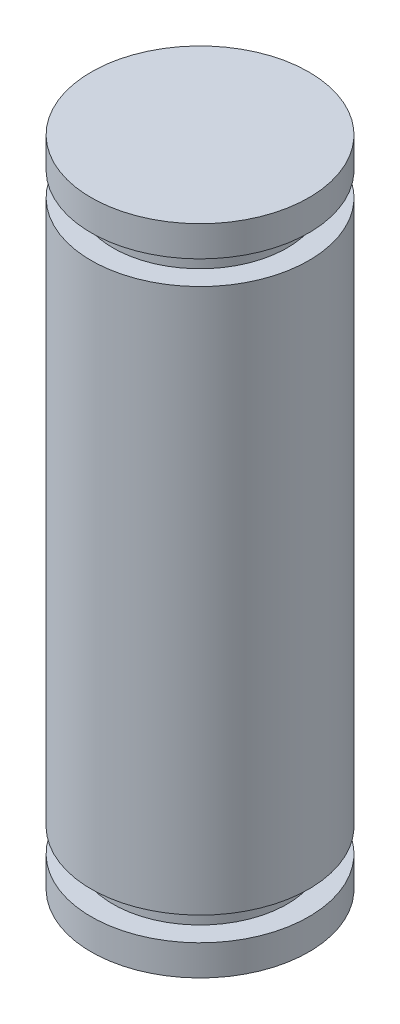
SolidWorks part; units mm, degrees
ref_plane "前视基准面" through (0, 0, 0) normal (0, 0, 1) x (1, 0, 0)
ref_plane "上视基准面" through (0, 0, 0) normal (0, 1, 0) x (1, 0, 0)
ref_plane "右视基准面" through (0, 0, 0) normal (1, 0, 0) x (0, 0, -1)
sketch "草图1" plane through (0, 0, 0) normal (0, 0, 1) x (1, 0, 0)
  line L0 (0, 0) -> (0, 30) construction
  line L1 (0, 0) -> (-5, 0)
  line L2 (-5, 0) -> (-5, 1.4)
  line L3 (-5, 1.4) -> (-4, 1.4)
  line L4 (-4, 1.4) -> (-4, 2.5)
  line L5 (-4, 2.5) -> (-5, 2.5)
  line L6 (-5, 2.5) -> (-5, 27.5)
  line L7 (-5, 27.5) -> (-4, 27.5)
  line L8 (-4, 27.5) -> (-4, 28.6)
  line L9 (-4, 28.6) -> (-5, 28.6)
  line L10 (-5, 28.6) -> (-5, 30)
  line L11 (-5, 30) -> (0, 30)
  line L12 (0, 0) -> (0, 30)
  dimension "D1" = 25
  dimension "D2" = 30
  dimension "D3" = 1.1
  dimension "D4" = 1.1
  dimension "D5" = 1
  dimension "D6" = 5
  dimension "D7" = 5
  dimension "D8" = 5
revolve "旋转1" add sketch "草图1" angle 360 about L0
